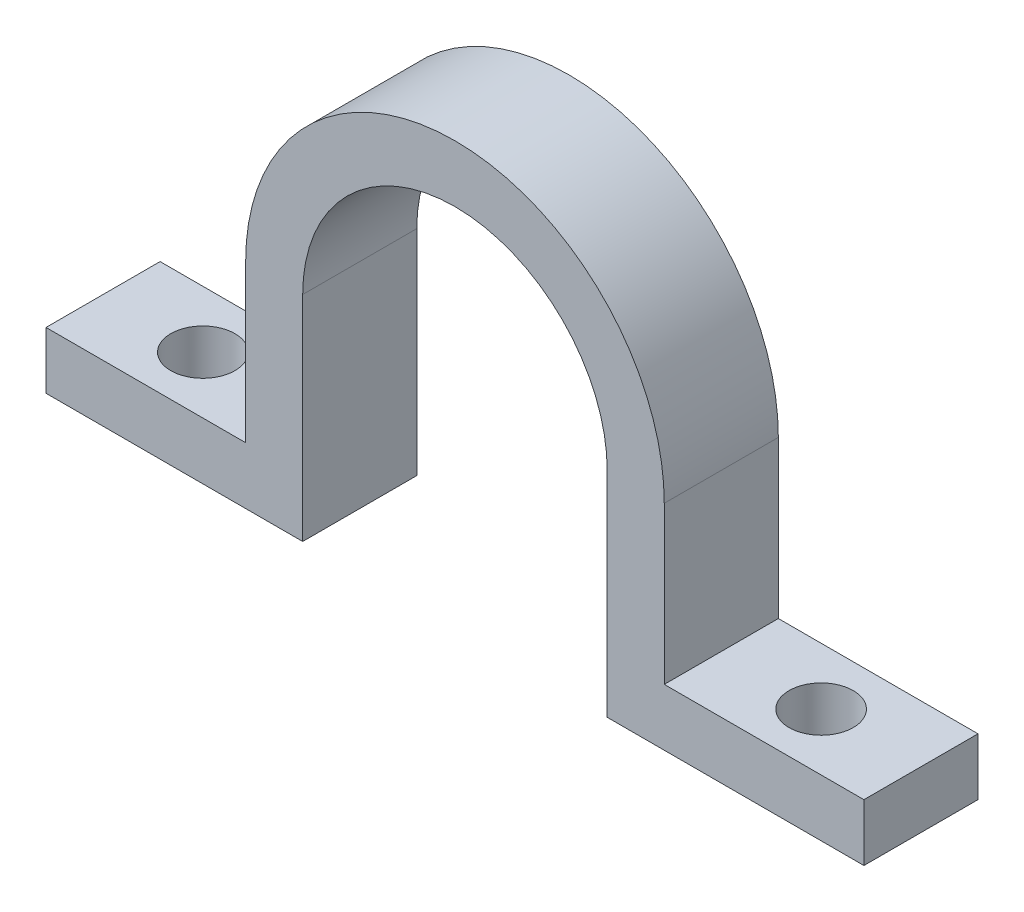
SolidWorks part; units mm, degrees
ref_plane "Front Plane" through (0, 0, 0) normal (0, 0, 1) x (1, 0, 0)
ref_plane "Top Plane" through (0, 0, 0) normal (0, 1, 0) x (1, 0, 0)
ref_plane "Right Plane" through (0, 0, 0) normal (1, 0, 0) x (0, 0, -1)
other "Configuration Table"
sketch "Sketch1" plane through (0, 0, 0) normal (0, 0, 1) x (1, 0, 0)
  line L0 (-28.6775, 0) -> (-10.6775, 0)
  line L1 (-10.6775, 0) -> (-10.6775, 15)
  line L2 (10.6775, 15) -> (10.6775, 0)
  line L3 (10.6775, 0) -> (28.6775, 0)
  line L4 (28.6775, 0) -> (28.6775, 4)
  line L5 (28.6775, 4) -> (14.6775, 4)
  line L6 (14.6775, 4) -> (14.6775, 15)
  line L7 (-14.6775, 15) -> (-14.6775, 4)
  line L8 (-14.6775, 4) -> (-28.6775, 4)
  line L9 (-28.6775, 4) -> (-28.6775, 0)
  arc A0 (-10.6775, 15) -> (10.6775, 15) centre (0, 15) cw
  arc A1 (14.6775, 15) -> (-14.6775, 15) centre (0, 15) ccw
extrude "Strap" add sketch "Sketch1" along normal mid plane 8
sketch "Sketch2" plane through (0, 0, 0) normal (0, 1, 0) x (1, 0, 0)
  circle A0 centre (-21.6775, 0) radius 2.25
  circle A1 centre (21.6775, 0) radius 2.25
  dimension "D1" = 4.5
  dimension "D2" = 4.5
extrude "Ear_Holes_M4" cut sketch "Sketch2" along normal blind 5 from offset 0.5
equation "\"Jar_OD\"= 90  'ASSUMED - Part G fallback - jar outer diameter"
equation "\"Jar_H\"= 120  'ASSUMED - Part G fallback - jar height"
equation "\"Pump_L\"= 45  'ASSUMED - Part G fallback"
equation "\"Pump_W\"= 24  'ASSUMED - Part G fallback"
equation "\"Pump_H\"= 33  'ASSUMED - Part G fallback"
equation "\"Pump_Outlet_OD\"= 7.5  'ASSUMED - Part G fallback"
equation "\"Tube_OD\"= 8  'ASSUMED - Part G fallback"
equation "\"Tube_ID\"= 6  'ASSUMED - Part G fallback"
equation "\"TDS_Body_Dia\"= 12  'ASSUMED - Part G fallback"
equation "\"TDS_Wet_Len\"= 45  'ASSUMED - Part G fallback - length in water"
equation "\"DS_Tube_Dia\"= 6  'ASSUMED - Part G fallback"
equation "\"DS_Tube_Len\"= 50  'ASSUMED - Part G fallback"
equation "\"ORP_Body_Dia\"= 12  'ASSUMED - Part G fallback"
equation "\"ORP_Body_Len\"= 150  'ASSUMED - Part G fallback"
equation "\"ORP_Cap_Dia\"= 16  'ASSUMED - Part G fallback"
equation "\"Turb_W\"= 33  'ASSUMED - Part G fallback - head width"
equation "\"Turb_D\"= 28  'ASSUMED - Part G fallback - head depth"
equation "\"Turb_H\"= 30  'ASSUMED - Part G fallback - head height"
equation "\"Turb_Slot_W\"= 10  'ASSUMED - Part G fallback - slot width"
equation "\"Flow_L\"= 62  'ASSUMED - Part G fallback YF-S201"
equation "\"Flow_W\"= 36  'ASSUMED - Part G fallback"
equation "\"Flow_H\"= 35  'ASSUMED - Part G fallback"
equation "\"Thread_G12_OD\"= 20.955  'ASSUMED - Part G fallback thread G1/2 (major diameter)"
equation "\"Valve_L\"= 75  'ASSUMED - Part G fallback"
equation "\"Valve_W\"= 45  'ASSUMED - Part G fallback"
equation "\"Valve_H\"= 60  'ASSUMED - Part G fallback"
equation "\"Tee_L\"= 40  'ASSUMED - Part G fallback - overall length"
equation "\"Tee_Branch_L\"= 25  'ASSUMED - Part G fallback"
equation "\"Tee_OD\"= 12  'ASSUMED - Part G fallback"
equation "\"LED_Board_L\"= 20  'ASSUMED - Part G fallback"
equation "\"LED_Board_W\"= 20  'ASSUMED - Part G fallback - LED at centre"
equation "\"GUVA_L\"= 20  'ASSUMED - Part G fallback"
equation "\"GUVA_W\"= 12  'ASSUMED - Part G fallback - sensor at centre"
equation "\"Reed_L\"= 27  'ASSUMED - Part G fallback MC-38 half"
equation "\"Reed_W\"= 14  'ASSUMED - Part G fallback"
equation "\"Reed_H\"= 8  'ASSUMED - Part G fallback"
equation "\"ESP_L\"= 51  'ASSUMED - Part G fallback"
equation "\"ESP_W\"= 28  'ASSUMED - Part G fallback"
equation "\"TFT_L\"= 58  'ASSUMED - Part G fallback - board"
equation "\"TFT_W\"= 35  'ASSUMED - Part G fallback - board"
equation "\"TFT_Win_L\"= 35  'ASSUMED - Part G fallback - visible window"
equation "\"TFT_Win_W\"= 28  'ASSUMED - Part G fallback - visible window"
equation "\"Relay_L\"= 50  'ASSUMED - Part G fallback"
equation "\"Relay_W\"= 26  'ASSUMED - Part G fallback"
equation "\"Relay_H\"= 19  'ASSUMED - Part G fallback"
equation "\"Mosfet_L\"= 34  'ASSUMED - Part G fallback"
equation "\"Mosfet_W\"= 17  'ASSUMED - Part G fallback"
equation "\"Mosfet_H\"= 12  'ASSUMED - Part G fallback"
equation "\"TDS_Board_L\"= 42  'ASSUMED - Part G fallback"
equation "\"TDS_Board_W\"= 32  'ASSUMED - Part G fallback"
equation "\"Turb_Board_L\"= 38  'ASSUMED - Part G fallback"
equation "\"Turb_Board_W\"= 28  'ASSUMED - Part G fallback"
equation "\"BNC_Thread_Dia\"= 9.5  'ASSUMED - Part G fallback"
equation "\"Plate_L\"= 420  'ASSUMED - Part G fallback"
equation "\"Plate_W\"= 297  'ASSUMED - Part G fallback"
equation "\"Plate_T\"= 6  'ASSUMED - Part G fallback"
equation "\"Booster_L\"= 150  'ASSUMED - Part G fallback - booster pump"
equation "\"Booster_W\"= 95  'ASSUMED - Part G fallback"
equation "\"Booster_H\"= 100  'ASSUMED - Part G fallback"
equation "\"PTube_OD\"= 6.35  'ASSUMED - Part G fallback - product tube 1/4 inch"
equation "\"Qz_Out\"= 12  'ASSUMED - Part G fallback - quartz channel outside square"
equation "\"Qz_Path\"= 10  'ASSUMED - Part G fallback - quartz channel inside light path"
equation "\"Qz_L\"= 40  'ASSUMED - Part G fallback - quartz channel length"
equation "\"LED860_Dia\"= 5  'ASSUMED - Part G fallback - 860 nm LED"
equation "\"BPW_L\"= 5.4  'ASSUMED - Part G fallback - BPW34"
equation "\"BPW_W\"= 4.3  'ASSUMED - Part G fallback - BPW34"
equation "\"Cart_Dia\"= 50  'ASSUMED - Part G fallback - sediment and pre-carbon cartridges"
equation "\"Cart_L\"= 255  'ASSUMED - Part G fallback"
equation "\"UF_Dia\"= 50  'ASSUMED - Part G fallback - UF cartridge"
equation "\"UF_L\"= 260  'ASSUMED - Part G fallback"
equation "\"RO_Dia\"= 62  'ASSUMED - Part G fallback - RO membrane housing"
equation "\"RO_L\"= 300  'ASSUMED - Part G fallback"
equation "\"UVC_Dia\"= 40  'ASSUMED - Part G fallback - UV-C chamber"
equation "\"UVC_L\"= 300  'ASSUMED - Part G fallback"
equation "\"Tank_W\"= 260  'ASSUMED - Part G fallback - storage tank"
equation "\"Tank_D\"= 160  'ASSUMED - Part G fallback"
equation "\"Tank_H\"= 300  'ASSUMED - Part G fallback"
equation "\"Cab_W\"= 400  'ASSUMED - Part G fallback - purifier cabinet"
equation "\"Cab_D\"= 270  'ASSUMED - Part G fallback"
equation "\"Cab_H\"= 560  'ASSUMED - Part G fallback"
equation "\"ORP_Board_L\"= 40  'ASSUMED - Part G fallback - ORP buffer board"
equation "\"ORP_Board_W\"= 30  'ASSUMED - Part G fallback"
equation "\"Opt_Board_L\"= 50  'ASSUMED - Part G fallback - optical front-end board"
equation "\"Opt_Board_W\"= 40  'ASSUMED - Part G fallback"
equation "\"Buck_L\"= 43  'ASSUMED - Part G fallback - 12 V to 5 V buck module"
equation "\"Buck_W\"= 21  'ASSUMED - Part G fallback"
equation "\"Buck_H\"= 14  'ASSUMED - Part G fallback"
equation "\"BB_L\"= 165  'ASSUMED - Part G fallback - breadboard (As_Built_R3 only)"
equation "\"BB_W\"= 55  'ASSUMED - Part G fallback"
equation "\"BB_H\"= 10  'ASSUMED - Part G fallback"
equation "\"Cuv_W\"= 12.5  'ASSUMED - old R3 cuvette (station suppressed in SS4)"
equation "\"Cuv_D\"= 12.5  'ASSUMED - old R3 cuvette (station suppressed in SS4)"
equation "\"Cuv_H\"= 45  'ASSUMED - old R3 cuvette (station suppressed in SS4)"
equation "\"Probe_Clr\"= 0.3  'DESIGN VALUE - Part C rule 3 - printed probe hole = diameter + 0.3"
equation "\"Label_H\"= 0.6  'DESIGN VALUE - Part D - raised label height"
